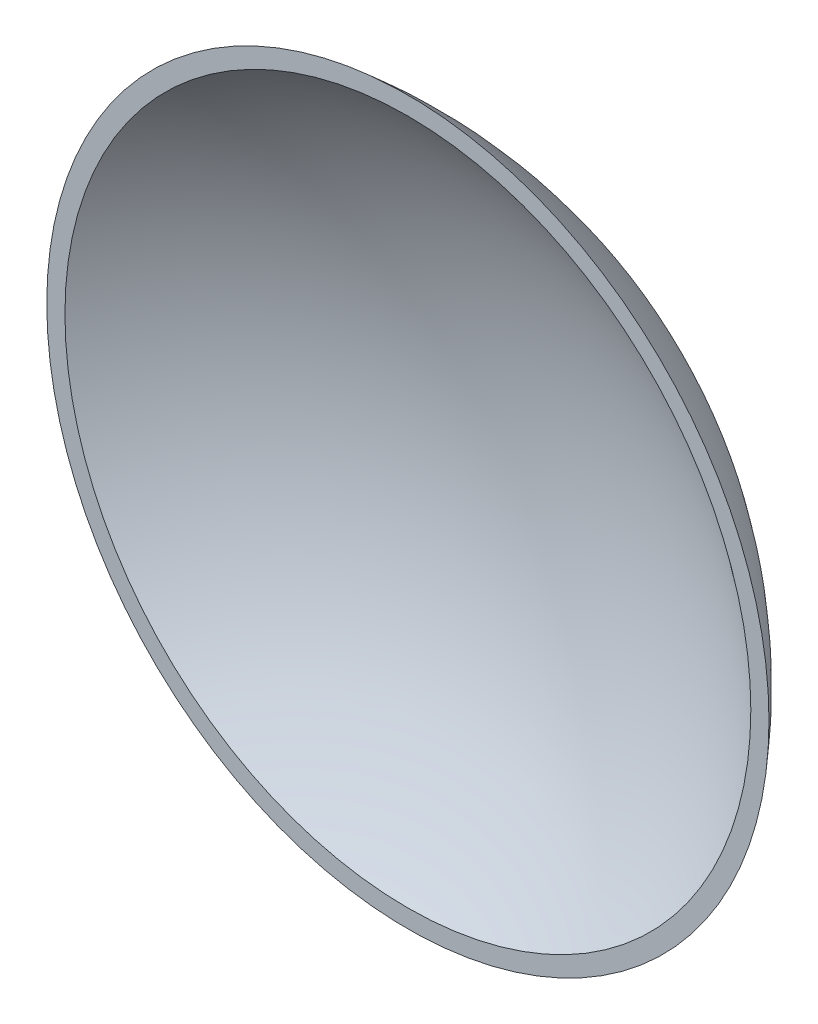
SolidWorks part; units mm, degrees
material "ABS PC"
ref_plane "Front Plane" through (0, 0, 0) normal (0, 0, 1) x (1, 0, 0)
ref_plane "Top Plane" through (0, 0, 0) normal (0, 1, 0) x (1, 0, 0)
ref_plane "Right Plane" through (0, 0, 0) normal (1, 0, 0) x (0, 0, -1)
sketch "Sketch2" plane through (0, 0, 0) normal (0, 1, 0) x (1, 0, 0)
  line L0 (0, 0) -> (0, 26.3009) construction
  line L1 (0, 26.3009) -> (0, 19.8399)
  line L2 (-48.2448, 2.6219) -> (-50.8, 2.6219)
  line L3 (-48.2448, 2.6219) -> (50.739, 2.6219) construction
  arc A0 (0, 19.8399) -> (-48.2448, 2.6219) centre (0, -56.3601) ccw
  arc A1 (0, 26.3009) -> (-50.8, 2.6219) centre (0, -40.0308) ccw
  point P7 (0, 2.6219)
  dimension "D2" = 76.2
  dimension "D1" = 101.6
  dimension "D3" = 48.2448
  dimension "D4" = 17.218
revolve "Revolve1" add sketch "Sketch2" angle 360 about L0
